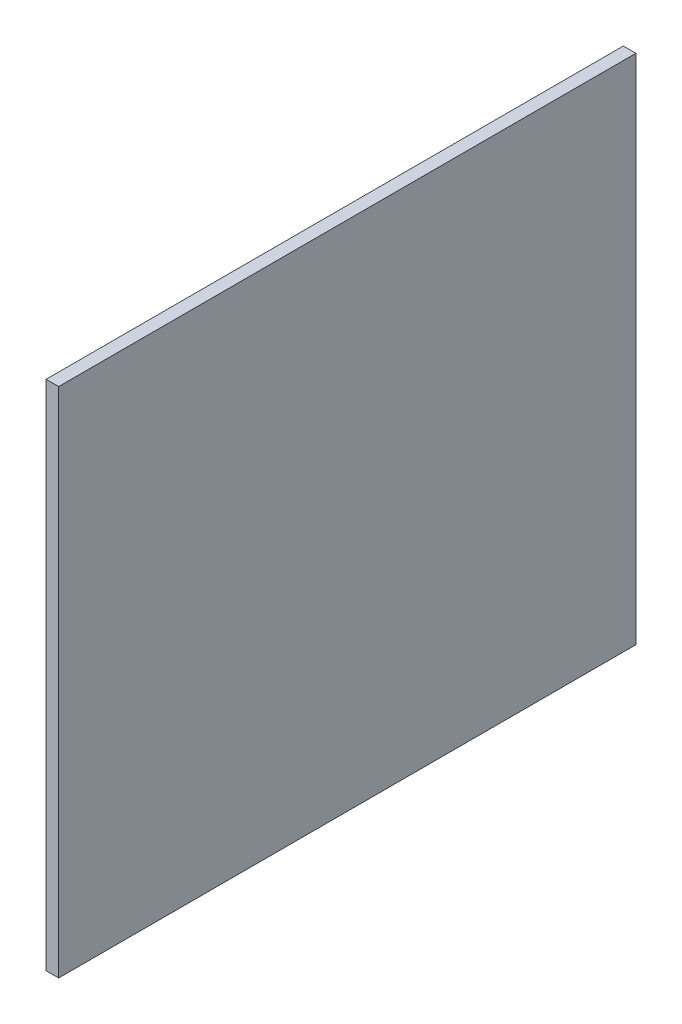
SolidWorks part; units mm, degrees
ref_plane "Front Plane" through (0, 0, 0) normal (0, 0, 1) x (1, 0, 0)
ref_plane "Top Plane" through (0, 0, 0) normal (0, 1, 0) x (1, 0, 0)
ref_plane "Right Plane" through (0, 0, 0) normal (1, 0, 0) x (0, 0, -1)
sketch "Sketch1" plane through (0, 0, 0) normal (0, 0, 1) x (1, 0, 0)
  line L1 (-90.4615, 111.6923) -> (-78.4615, 111.6923)
  line L2 (-90.4615, 111.6923) -> (-90.4615, -376.3077)
  line L3 (-90.4615, -376.3077) -> (-78.4615, -376.3077)
  line L4 (-78.4615, 111.6923) -> (-78.4615, -376.3077)
  dimension "D1" = 12
  dimension "D2" = 488
extrude "Boss-Extrude1" add sketch "Sketch1" along normal blind 550
